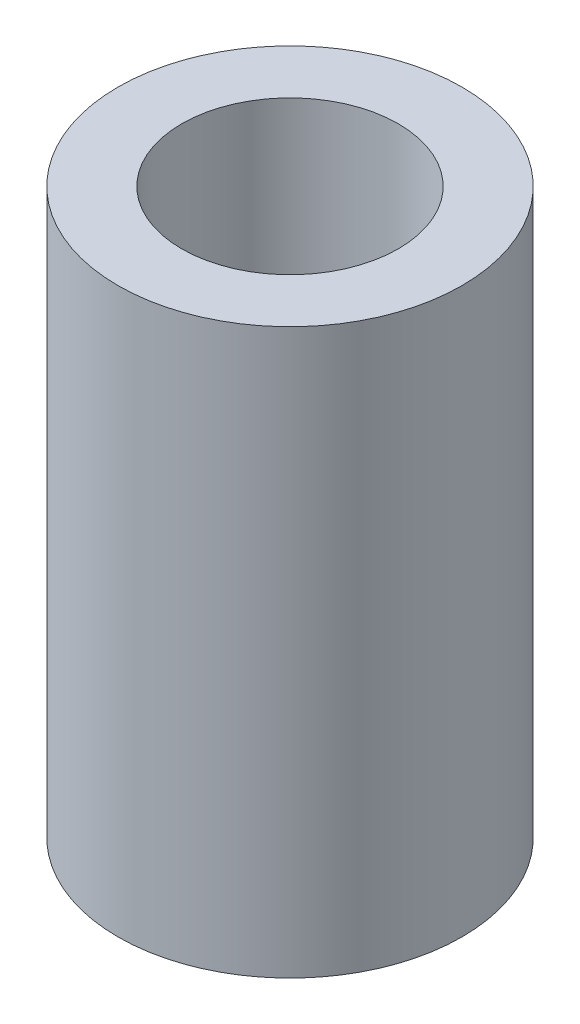
SolidWorks part; units mm, degrees
material "Custom Plastic"
ref_plane "X-Y Datum" through (0, 0, 0) normal (0, 0, 1) x (1, 0, 0)
ref_plane "X-Z Datum" through (0, 0, 0) normal (0, 1, 0) x (1, 0, 0)
ref_plane "Y-Z Datum" through (0, 0, 0) normal (1, 0, 0) x (0, 0, -1)
sketch "Sketch2" plane through (0, 0, 0) normal (0, 1, 0) x (1, 0, 0)
  circle A0 centre (0, 0) radius 3.175
  circle A1 centre (0, 0) radius 2
  dimension "D1" = 4
  dimension "D2" = 6.35
extrude "Boss-Extrude1" add sketch "Sketch2" against normal blind 10.414
